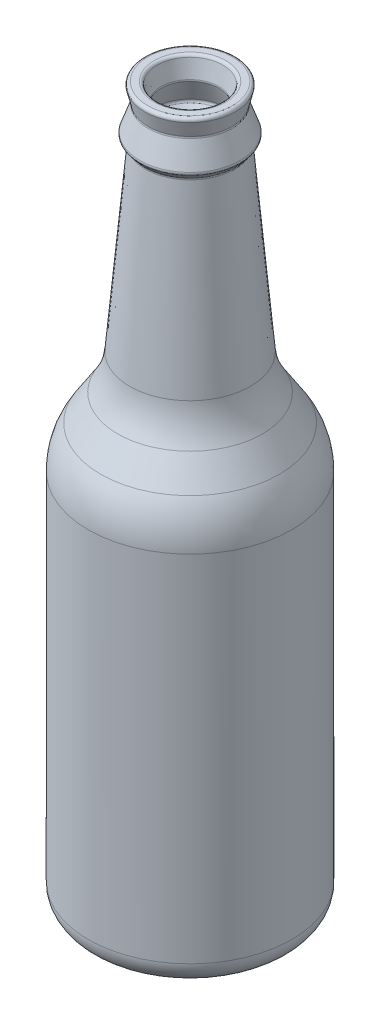
SolidWorks part; units mm, degrees
other "Camera1"
ref_plane "Front" through (0, 0, 0) normal (0, 0, 1) x (1, 0, 0)
ref_plane "Top" through (0, 0, 0) normal (0, 1, 0) x (1, 0, 0)
ref_plane "Right" through (0, 0, 0) normal (1, 0, 0) x (0, 0, -1)
sketch "Sketch4" plane through (0, 0, 0) normal (0, 0, 1) x (1, 0, 0)
  line L0 (0, 0) -> (0, 255.2988) construction
  line L1 (0, 0) -> (25.1705, 0)
  line L2 (32.7909, 7.6204) -> (32.7909, 129.3269)
  line L3 (32.7909, 129.3269) -> (19.9943, 149.2167)
  line L4 (19.9943, 149.2167) -> (14.3242, 213.8141)
  line L5 (14.3242, 213.8141) -> (16.3712, 216.255)
  line L6 (16.3712, 216.255) -> (13.4176, 224.6347)
  line L7 (13.4176, 224.6347) -> (14.8944, 230.7958)
  line L8 (14.8944, 230.7958) -> (0, 230.7958)
  line L9 (0, 230.7958) -> (0, 0)
  arc A0 (25.1705, 0) -> (32.7909, 7.6204) centre (25.1705, 7.6204) ccw
revolve "Revolve2" add sketch "Sketch4" angle 360 about L0
shell "Shell2" thickness 4
fillet "Fillet4" radius 25 2 edges at (0, 149.2167, -19.9943) (0, 129.3269, -32.7909)
fillet "Fillet5" radius 1 8 edges at (0, 224.4188, -9.2526) (0, 217.0771, -11.8402) (0, 215.1148, -10.1946) (0, 230.7958, 10.7811) (0, 230.7958, -14.8944) (0, 224.6347, -13.4176) (0, 216.255, -16.3712) (0, 213.8141, -14.3242)
